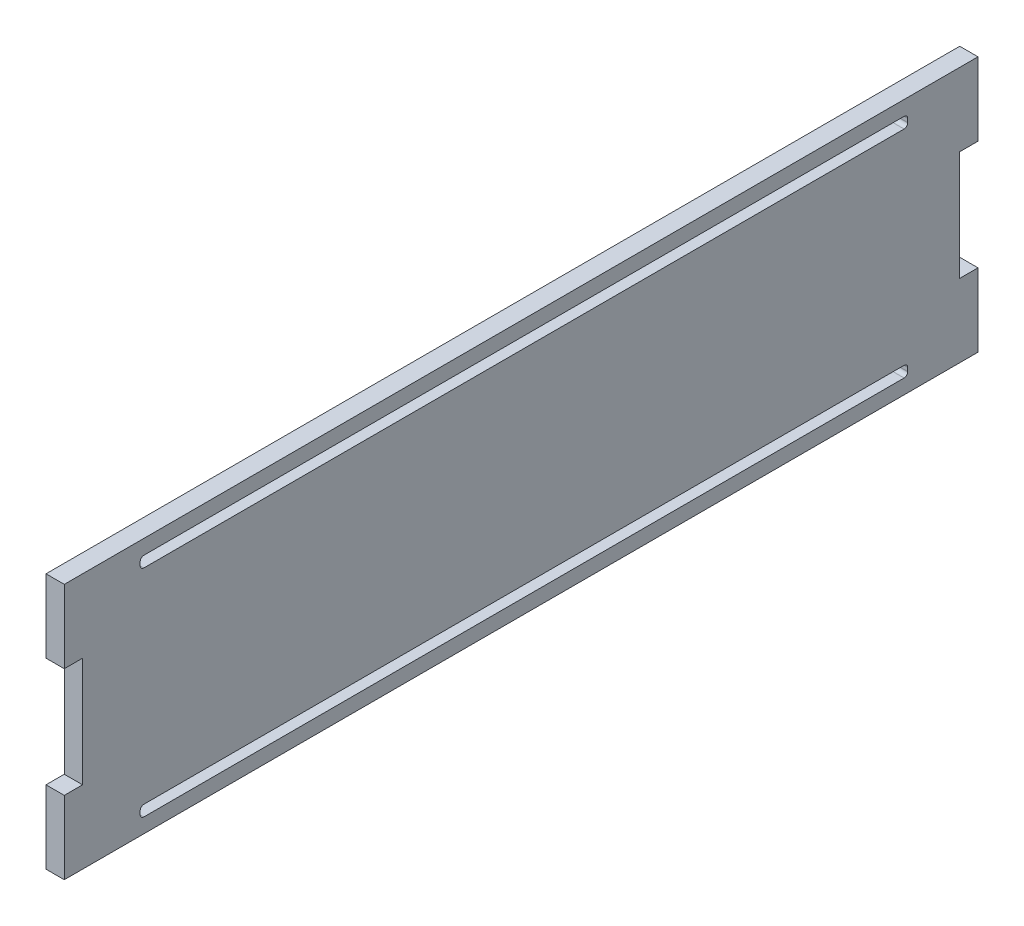
SolidWorks part; units mm, degrees
ref_plane "前视基准面" through (0, 0, 0) normal (0, 0, 1) x (1, 0, 0)
ref_plane "上视基准面" through (0, 0, 0) normal (0, 1, 0) x (1, 0, 0)
ref_plane "右视基准面" through (0, 0, 0) normal (1, 0, 0) x (0, 0, -1)
sketch "草图1" plane through (0, 0, 0) normal (1, 0, 0) x (0, 0, -1)
  line L0 (-245, 93.5835) -> (-245, 70) construction
  line L1 (0, 0) -> (-250, 0)
  line L2 (0, 0) -> (0, 20)
  line L3 (0, 70) -> (-250, 70)
  line L4 (-250, 0) -> (-250, 20)
  line L5 (-5, -59.5797) -> (-5, 0) construction
  line L6 (-272.3265, 50) -> (69.7825, 50) construction
  line L7 (-266.9759, 20) -> (67.1072, 20) construction
  line L8 (-250, 50) -> (-250, 70)
  line L9 (-245, 50) -> (-250, 50)
  line L10 (-250, 20) -> (-245, 20)
  line L11 (-264.259, 64.5) -> (-261.259, 64.5) construction
  line L12 (-266.9759, 5.5) -> (56.8304, 5.5) construction
  line L13 (0, 20) -> (-5, 20)
  line L14 (0, 50) -> (0, 70)
  line L15 (-5, 50) -> (0, 50)
  line L16 (-245, 50) -> (-245, 20)
  line L18 (-245, 50) -> (-245, 20) construction
  line L19 (-245, 0) -> (-245, -65.2648) construction
  line L20 (-5, 70) -> (-5, 99.5797) construction
  line L21 (-228.2219, 66) -> (-20.2219, 66)
  line L22 (-229.2219, 65) -> (-229.2219, 64)
  line L23 (-228.2219, 63) -> (-20.2219, 63)
  line L24 (-19.2219, 65) -> (-19.2219, 64)
  line L25 (-229.2219, 66) -> (-19.2219, 63) construction
  line L26 (-229.2219, 63) -> (-19.2219, 66) construction
  line L27 (-228.2219, 4) -> (-20.2219, 4)
  line L28 (-229.2219, 5) -> (-229.2219, 6)
  line L29 (-228.2219, 7) -> (-20.2219, 7)
  line L30 (-19.2219, 5) -> (-19.2219, 6)
  line L31 (-229.2219, 4) -> (-19.2219, 7) construction
  line L32 (-229.2219, 7) -> (-19.2219, 4) construction
  line L33 (-5, 50) -> (-5, 20)
  arc A0 (-20.2219, 63) -> (-19.2219, 64) centre (-20.2219, 64) ccw
  arc A1 (-20.2219, 66) -> (-19.2219, 65) centre (-20.2219, 65) cw
  arc A2 (-20.2219, 4) -> (-19.2219, 5) centre (-20.2219, 5) ccw
  arc A3 (-20.2219, 7) -> (-19.2219, 6) centre (-20.2219, 6) cw
  arc A4 (-228.2219, 4) -> (-229.2219, 5) centre (-228.2219, 5) cw
  arc A5 (-229.2219, 6) -> (-228.2219, 7) centre (-228.2219, 6) cw
  arc A6 (-229.2219, 64) -> (-228.2219, 63) centre (-228.2219, 64) ccw
  arc A7 (-228.2219, 66) -> (-229.2219, 65) centre (-228.2219, 65) ccw
  point P29 (-124.2219, 64.5)
  point P34 (-124.2219, 5.5)
  dimension "D14" = 1
  dimension "D1" = 250
  dimension "D2" = 70
  dimension "D3" = 5
  dimension "D4" = 5
  dimension "D5" = 20
  dimension "D6" = 20
  dimension "D7" = 30
  dimension "D8" = 59
  dimension "D9" = 5.5
  dimension "D10" = 210
  dimension "D11" = 210
  dimension "D12" = 3
  dimension "D13" = 3
extrude "凸台-拉伸1" add sketch "草图1" along normal blind 5
